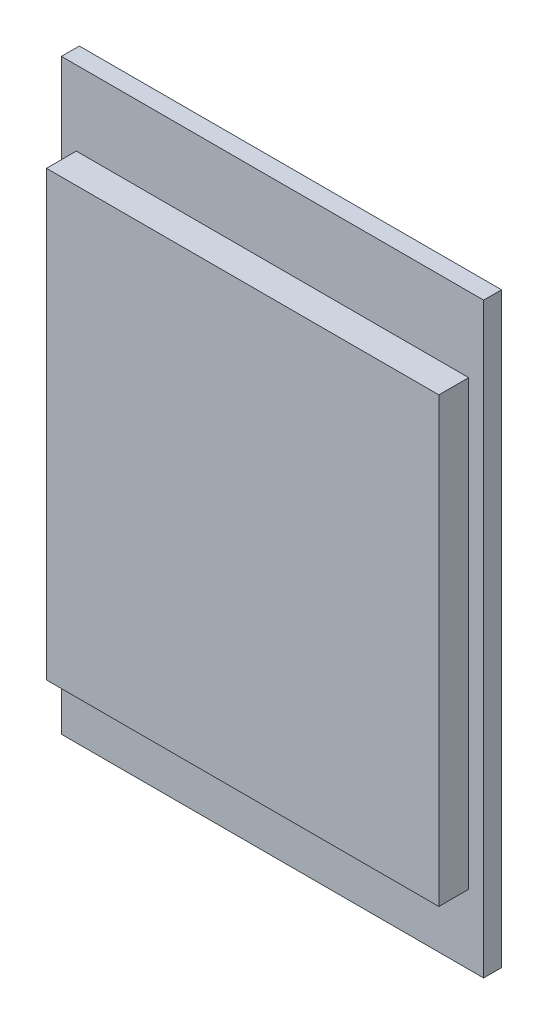
SolidWorks part; units mm, degrees
ref_plane "Спереди" through (0, 0, 0) normal (0, 0, 1) x (1, 0, 0)
ref_plane "Сверху" through (0, 0, 0) normal (0, 1, 0) x (1, 0, 0)
ref_plane "Справа" through (0, 0, 0) normal (1, 0, 0) x (0, 0, -1)
sketch "Эскиз1" plane through (0, 0, 0) normal (0, 0, 1) x (1, 0, 0)
  line L1 (-14.15, 19.675) -> (14.15, 19.675)
  line L2 (-14.15, 19.675) -> (-14.15, -19.675)
  line L3 (-14.15, -19.675) -> (14.15, -19.675)
  line L4 (14.15, 19.675) -> (14.15, -19.675)
  line L5 (-14.15, 19.675) -> (14.15, -19.675) construction
  line L6 (-14.15, -19.675) -> (14.15, 19.675) construction
  point P0 (0, 0)
  dimension "D1" = 28.3
  dimension "D2" = 39.35
extrude "Бобышка-Вытянуть1" add sketch "Эскиз1" along normal blind 1.2
sketch "Эскиз2" plane through (0, 0, 1.2) normal (0, 0, 1) x (1, 0, 0)
  line L0 (0, 19.675) -> (0, -19.675) construction
  line L1 (14.15, 19.675) -> (-14.15, 19.675) construction
  line L2 (-14.15, -19.675) -> (14.15, -19.675) construction
  line L4 (-13.15, 14.675) -> (13.15, 14.675)
  line L5 (-13.15, 14.675) -> (-13.15, -15.025)
  line L6 (-13.15, -15.025) -> (13.15, -15.025)
  line L7 (13.15, 14.675) -> (13.15, -15.025)
  line L8 (-13.15, 14.675) -> (13.15, -15.025) construction
  line L9 (-13.15, -15.025) -> (13.15, 14.675) construction
  point P6 (0, -0.175)
  dimension "D1" = 5
  dimension "D2" = 26.3
  dimension "D3" = 29.7
extrude "Бобышка-Вытянуть2" add sketch "Эскиз2" along normal blind 2
